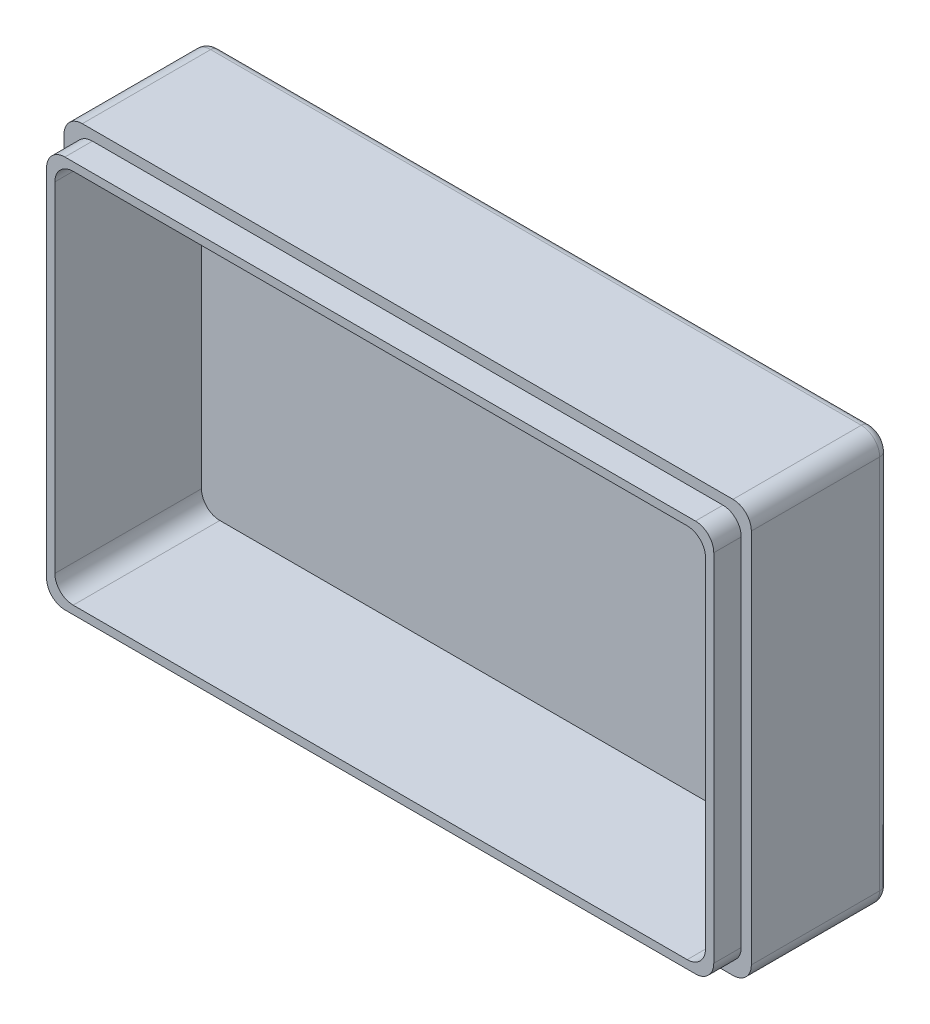
SolidWorks part; units mm, degrees
ref_plane "前视基准面" through (0, 0, 0) normal (0, 0, 1) x (1, 0, 0)
ref_plane "上视基准面" through (0, 0, 0) normal (0, 1, 0) x (1, 0, 0)
ref_plane "右视基准面" through (0, 0, 0) normal (1, 0, 0) x (0, 0, -1)
sketch "草图1" plane through (0, 0, 0) normal (0, 0, 1) x (1, 0, 0)
  line L1 (-37.5, 22.5) -> (37.5, 22.5)
  line L2 (-37.5, 22.5) -> (-37.5, -22.5)
  line L3 (-37.5, -22.5) -> (37.5, -22.5)
  line L4 (37.5, 22.5) -> (37.5, -22.5)
  dimension "D1" = 75
  dimension "D2" = 45
  dimension "D3" = 37.5
  dimension "D4" = 22.5
extrude "凸台-拉伸1" add sketch "草图1" along normal blind 18
sketch "草图2" plane through (0, 0, 18) normal (0, 0, 1) x (1, 0, 0)
  line L0 (-35.5, 20.5) -> (-35.5, -20.5)
  line L1 (-35.5, -20.5) -> (35.5, -20.5)
  line L2 (35.5, -20.5) -> (35.5, 20.5)
  line L3 (35.5, 20.5) -> (-35.5, 20.5)
extrude "切除-拉伸1" cut sketch "草图2" against normal blind 16
sketch "草图3" plane through (0, 0, 18) normal (0, 0, 1) x (1, 0, 0)
  line L0 (-37.5, -22.5) -> (37.5, -22.5) construction
  line L1 (37.5, -22.5) -> (37.5, 22.5) construction
  line L2 (37.5, 22.5) -> (-37.5, 22.5) construction
  line L3 (-37.5, 22.5) -> (-37.5, -22.5) construction
  line L4 (-37.5, -22.5) -> (37.5, -22.5)
  line L5 (37.5, -22.5) -> (37.5, 22.5)
  line L6 (37.5, 22.5) -> (-37.5, 22.5)
  line L7 (-37.5, 22.5) -> (-37.5, -22.5)
  line L8 (-36.4, -21.4) -> (36.4, -21.4)
  line L9 (36.4, -21.4) -> (36.4, 21.4)
  line L10 (36.4, 21.4) -> (-36.4, 21.4)
  line L11 (-36.4, 21.4) -> (-36.4, -21.4)
  dimension "D1" = 1.1
extrude "切除-拉伸2" cut sketch "草图3" against normal blind 3
fillet "圆角1" radius 2 12 edges at (35.5, 20.5, 10) (-35.5, 20.5, 10) (-35.5, -20.5, 10) (35.5, -20.5, 10) (36.4, 21.4, 16.5) (37.5, 22.5, 7.5) (36.4, -21.4, 16.5) (37.5, -22.5, 7.5) (-36.4, -21.4, 16.5) (-37.5, -22.5, 7.5) (-36.4, 21.4, 16.5) (-37.5, 22.5, 7.5)
fillet "圆角2" radius 1 8 edges at (-36.9142, 21.9142, 0) (-37.5, 0, 0) (-36.9142, -21.9142, 0) (0, -22.5, 0) (36.9142, -21.9142, 0) (37.5, 0, 0) (36.9142, 21.9142, 0) (0, 22.5, 0)
